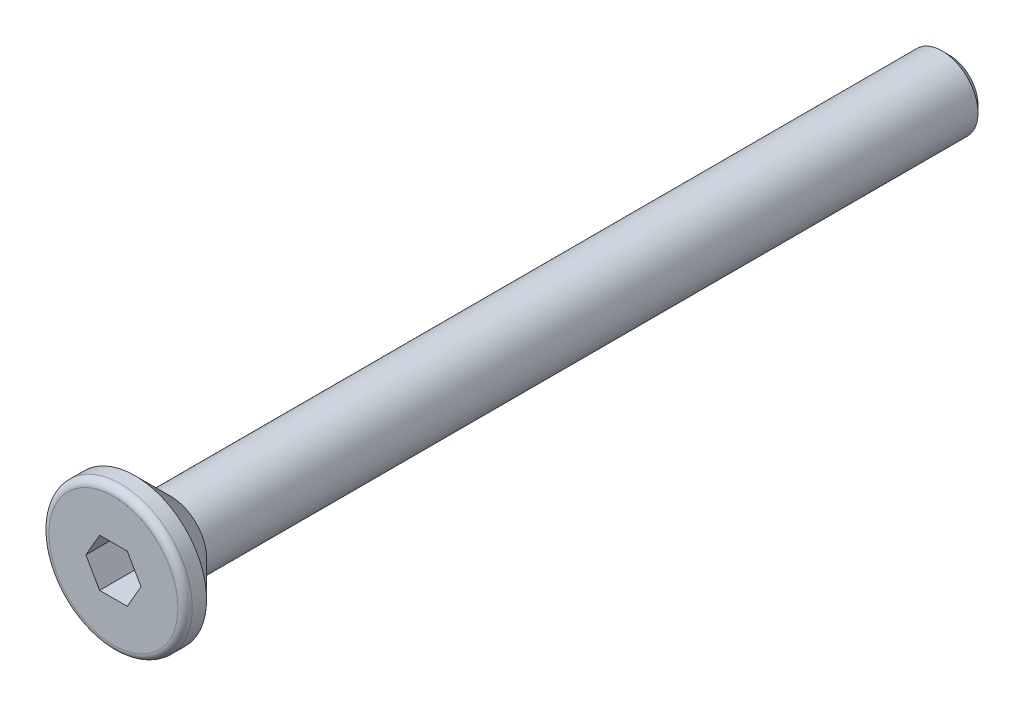
SolidWorks part; units mm, degrees
ref_plane "前视基准面" through (0, 0, 0) normal (0, 0, 1) x (1, 0, 0)
ref_plane "上视基准面" through (0, 0, 0) normal (0, 1, 0) x (1, 0, 0)
ref_plane "右视基准面" through (0, 0, 0) normal (1, 0, 0) x (0, 0, -1)
sketch "草图1" plane through (0, 0, 0) normal (1, 0, 0) x (0, 0, -1)
  line L0 (-17.5, 0) -> (-17.5, 3)
  line L1 (-17.5, 3) -> (-16.6, 3)
  line L2 (-16.6, 3) -> (-15.1, 1.5)
  line L3 (-15.1, 1.5) -> (17.2, 1.5)
  line L4 (17.2, 1.5) -> (17.5, 1.2)
  line L5 (17.5, 1.2) -> (17.5, 0)
  line L6 (17.5, 0) -> (-17.5, 0)
  dimension "D1" = 35
  dimension "D2" = 3
  dimension "D3" = 45
  dimension "D4" = 0.3
  dimension "D5" = 2.4
  dimension "D6" = 1.5
revolve "旋转1" add sketch "草图1" angle 360 about L6
sketch "草图2" plane through (0, 0, 17.5) normal (0, 0, 1) x (1, 0, 0)
  line L1 (1.1547, 0) -> (0.5774, 1)
  line L2 (0.5774, 1) -> (-0.5774, 1)
  line L3 (-0.5774, 1) -> (-1.1547, 0)
  line L4 (-1.1547, 0) -> (-0.5774, -1)
  line L5 (-0.5774, -1) -> (0.5774, -1)
  line L6 (0.5774, -1) -> (1.1547, 0)
  circle A0 centre (0, 0) radius 1 construction
  dimension "D1" = 2
extrude "切除-拉伸1" cut sketch "草图2" against normal blind 1.5
fillet "圆角1" radius 0.3 1 edges at (-3, 0, 17.5)
